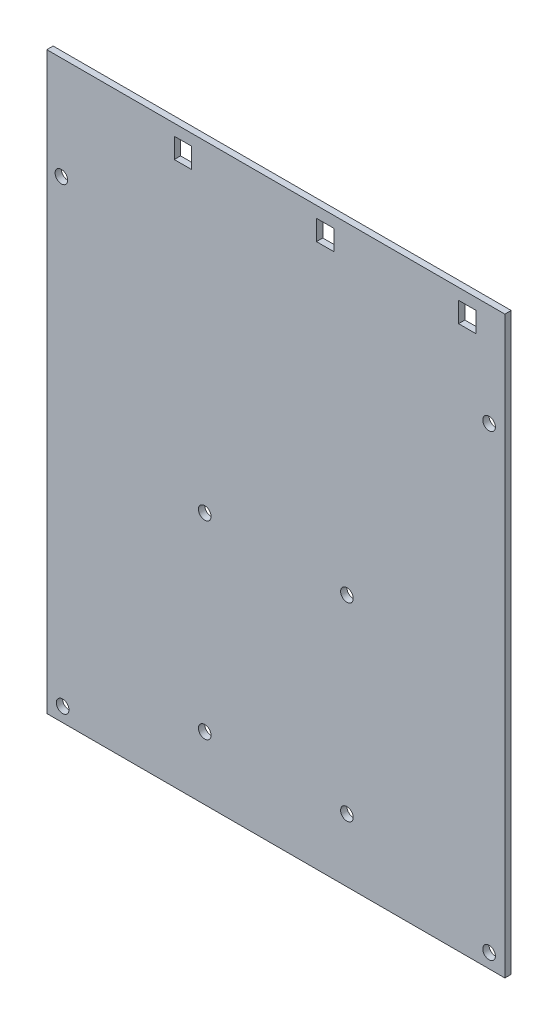
SolidWorks part; units mm, degrees
ref_plane "Płaszczyzna przednia" through (0, 0, 0) normal (0, 0, 1) x (1, 0, 0)
ref_plane "Płaszczyzna górna" through (0, 0, 0) normal (0, 1, 0) x (1, 0, 0)
ref_plane "Płaszczyzna prawa" through (0, 0, 0) normal (1, 0, 0) x (0, 0, -1)
sketch "Szkic1" plane through (0, 0, 0) normal (0, 0, 1) x (1, 0, 0)
  line L1 (72.5, 91) -> (-72.5, 91)
  line L2 (72.5, 91) -> (72.5, -91)
  line L3 (72.5, -91) -> (-72.5, -91)
  line L4 (-72.5, 91) -> (-72.5, -91)
  line L5 (72.5, 91) -> (-72.5, -91) construction
  line L6 (72.5, -91) -> (-72.5, 91) construction
  point P0 (0, 0)
  dimension "D1" = 145
  dimension "D2" = 182
extrude "Dodanie-wyciągnięcie1" add sketch "Szkic1" along normal blind 2
sketch "Szkic2" plane through (0, 0, 0) normal (0, 0, -1) x (-1, 0, 0)
  line L0 (22.5, -11) -> (22.5, -71) construction
  line L1 (22.5, -71) -> (-22.5, -71) construction
  line L2 (-22.5, -71) -> (-22.5, -11) construction
  line L3 (-22.5, -11) -> (22.5, -11) construction
  line L4 (0, 0) -> (0, -71) construction
  circle A4 centre (-22.5, -11) radius 2
  circle A5 centre (-22.5, -71) radius 2
  circle A6 centre (22.5, -71) radius 2
  circle A7 centre (22.5, -11) radius 2
  dimension "D1" = 4
  dimension "D2" = 60
  dimension "D3" = 45
  dimension "D4" = 11
extrude "Wytnij-wyciągnięcie1" cut sketch "Szkic2" against normal blind 32
sketch "Szkic3" plane through (0, 0, 0) normal (0, 0, -1) x (-1, 0, 0)
  line L0 (-18.35, 87.45) -> (-18.35, 81.05)
  line L1 (-12.85, 87.45) -> (-18.35, 87.45)
  line L2 (-12.85, 87.45) -> (-12.85, 81.05)
  line L3 (-12.85, 81.05) -> (-18.35, 81.05)
  line L4 (-62.35, 82.05) -> (-58.85, 82.05) construction
  line L5 (-58.85, 82.05) -> (-58.85, 86.45) construction
  line L6 (-62.35, 86.45) -> (-62.35, 82.05) construction
  line L7 (-58.85, 86.45) -> (-62.35, 86.45) construction
  line L8 (-60.6, 86.45) -> (-60.6, 82.05) construction
  line L9 (-62.35, 84.25) -> (-58.85, 84.25) construction
  line L10 (26.65, 87.45) -> (26.65, 81.05)
  line L11 (-57.85, 87.45) -> (-63.35, 87.45)
  line L12 (-57.85, 87.45) -> (-57.85, 81.05)
  line L13 (-57.85, 81.05) -> (-63.35, 81.05)
  line L14 (-63.35, 87.45) -> (-63.35, 81.05)
  line L15 (-57.85, 87.45) -> (-63.35, 81.05) construction
  line L16 (-57.85, 81.05) -> (-63.35, 87.45) construction
  line L17 (32.15, 87.45) -> (26.65, 87.45)
  line L18 (32.15, 87.45) -> (32.15, 81.05)
  line L19 (32.15, 81.05) -> (26.65, 81.05)
  point P8 (-60.6, 84.25)
  dimension "D1" = 60.6
  dimension "D2" = 84.25
  dimension "D3" = 4.4
  dimension "D4" = 3.5
  dimension "D5" = 1
  dimension "D6" = 1
  dimension "D7" = 3
extrude "Wytnij-wyciągnięcie2" cut sketch "Szkic3" against normal blind 32
sketch "Szkic4" plane through (0, 0, 0) normal (0, 0, -1) x (-1, 0, 0)
  circle A4 centre (67.5, -86.5) radius 2
  circle A5 centre (-67.5, -86.5) radius 2
  circle A6 centre (-67.5, 58.5) radius 2
  circle A7 centre (67.8787, 58.5) radius 2
extrude "Wytnij-wyciągnięcie3" cut sketch "Szkic4" against normal blind 12
